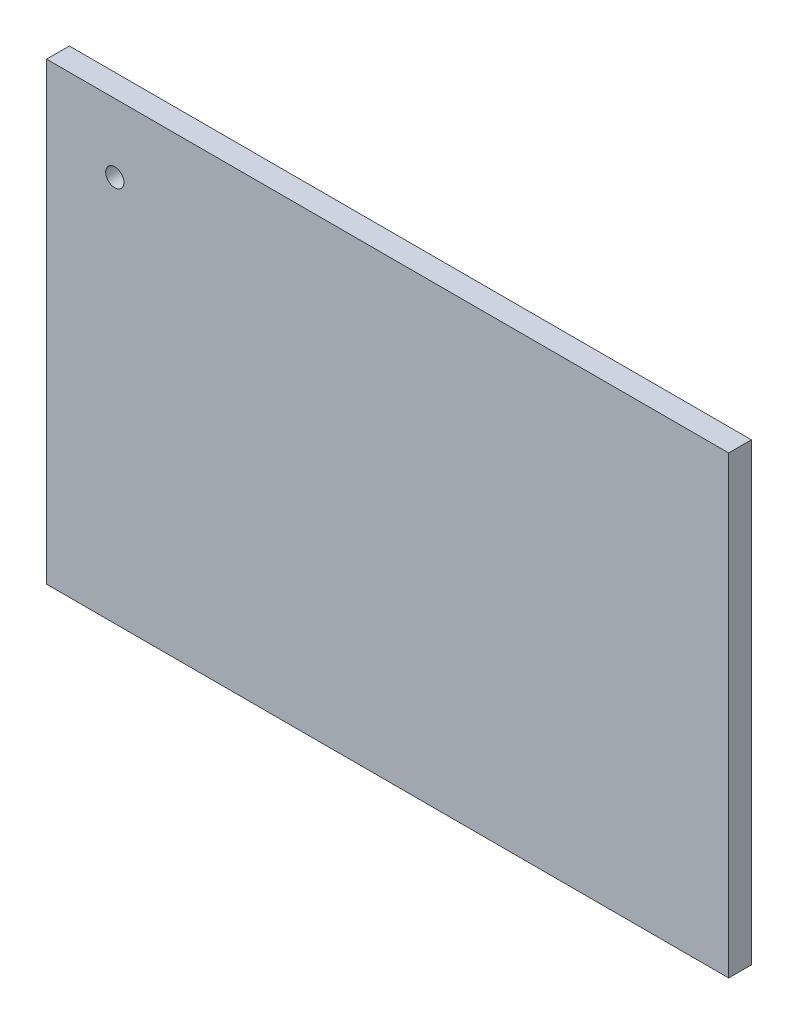
SolidWorks part; units mm, degrees
ref_plane "前视基准面" through (0, 0, 0) normal (0, 0, 1) x (1, 0, 0)
ref_plane "上视基准面" through (0, 0, 0) normal (0, 1, 0) x (1, 0, 0)
ref_plane "右视基准面" through (0, 0, 0) normal (1, 0, 0) x (0, 0, -1)
other "Configuration Table"
sketch "草图1" plane through (0, 0, 0) normal (0, 0, 1) x (1, 0, 0)
  line L1 (-150, 100) -> (150, 100)
  line L2 (-150, 100) -> (-150, -100)
  line L3 (-150, -100) -> (150, -100)
  line L4 (150, 100) -> (150, -100)
  line L5 (-150, 100) -> (150, -100) construction
  line L6 (-150, -100) -> (150, 100) construction
  point P0 (0, 0)
  dimension "D1" = 200
  dimension "D2" = 300
extrude "凸台-拉伸1" add sketch "草图1" along normal blind 10
sketch "草图2" plane through (0, 0, 10) normal (0, 0, 1) x (1, 0, 0)
  line L0 (-150, 100) -> (-150, -100) construction
  line L1 (150, 100) -> (-150, 100) construction
  circle A0 centre (-120, 70) radius 4
  point P6 (-89.4002, 100)
  dimension "D1" = 8
  dimension "D2" = 30
  dimension "D3" = 30
extrude "切除-拉伸1" cut sketch "草图2" against normal blind 10
